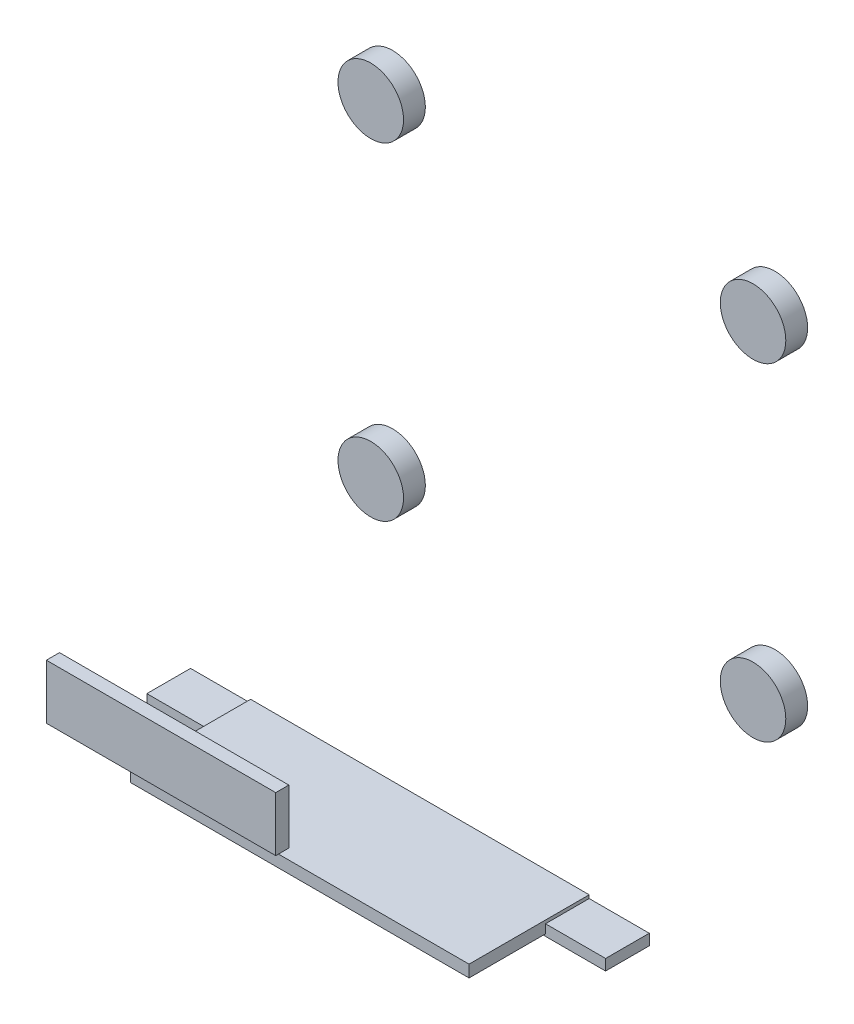
SolidWorks part; units mm, degrees
ref_plane "前视基准面" through (0, 0, 0) normal (0, 0, 1) x (1, 0, 0)
ref_plane "上视基准面" through (0, 0, 0) normal (0, 1, 0) x (1, 0, 0)
ref_plane "右视基准面" through (0, 0, 0) normal (1, 0, 0) x (0, 0, -1)
other "Configuration Table"
sketch "草图1" plane through (0, 0, 0) normal (0, 0, 1) x (1, 0, 0)
  line L1 (-31, -52.1) -> (31, -52.1)
  line L2 (-31, -52.1) -> (-31, -49.9)
  line L3 (-31, -49.9) -> (31, -49.9)
  line L4 (31, -52.1) -> (31, -49.9)
  line L5 (-31, -52.1) -> (31, -49.9) construction
  line L6 (-31, -49.9) -> (31, -52.1) construction
  point P0 (0, -51)
extrude "front face trim around HC-SR04 eye window" add sketch "草图1" along normal blind 22 from offset 26 separate body
sketch "草图2" plane through (0, 0, 0) normal (0, 0, 1) x (1, 0, 0)
  line L1 (-21, -25) -> (21, -25)
  line L2 (-21, -25) -> (-21, -15)
  line L3 (-21, -15) -> (21, -15)
  line L4 (21, -25) -> (21, -15)
  line L5 (-21, -25) -> (21, -15) construction
  line L6 (-21, -15) -> (21, -25) construction
  point P0 (0, -20)
extrude "top translucent status light strip" add sketch "草图2" along normal blind 2.4 from offset 71 separate body
sketch "草图3" plane through (0, 0, 0) normal (0, 0, 1) x (1, 0, 0)
  line L1 (-42, -52.5) -> (-30, -52.5)
  line L2 (-42, -52.5) -> (-42, -50.5)
  line L3 (-42, -50.5) -> (-30, -50.5)
  line L4 (-30, -52.5) -> (-30, -50.5)
  line L5 (-42, -52.5) -> (-30, -50.5) construction
  line L6 (-42, -50.5) -> (-30, -52.5) construction
  point P0 (-36, -51.5)
extrude "left cheek decorative insert" add sketch "草图3" along normal blind 8 from offset 26 separate body
sketch "草图4" plane through (0, 0, 0) normal (0, 0, 1) x (1, 0, 0)
  line L1 (30, -52.5) -> (42, -52.5)
  line L2 (30, -52.5) -> (30, -50.5)
  line L3 (30, -50.5) -> (42, -50.5)
  line L4 (42, -52.5) -> (42, -50.5)
  line L5 (30, -52.5) -> (42, -50.5) construction
  line L6 (30, -50.5) -> (42, -52.5) construction
  point P0 (36, -51.5)
extrude "right cheek decorative insert" add sketch "草图4" along normal blind 8 from offset 26 separate body
sketch "草图5" plane through (0, 0, 0) normal (0, 0, 1) x (1, 0, 0)
  circle A0 centre (-35, -30) radius 6
extrude "rubber foot 1" add sketch "草图5" along normal blind 4 from offset 4 separate body
sketch "草图6" plane through (0, 0, 0) normal (0, 0, 1) x (1, 0, 0)
  circle A0 centre (35, -30) radius 6
extrude "rubber foot 2" add sketch "草图6" along normal blind 4 from offset 4 separate body
sketch "草图7" plane through (0, 0, 0) normal (0, 0, 1) x (1, 0, 0)
  circle A0 centre (-35, 30) radius 6
extrude "rubber foot 3" add sketch "草图7" along normal blind 4 from offset 4 separate body
sketch "草图8" plane through (0, 0, 0) normal (0, 0, 1) x (1, 0, 0)
  circle A0 centre (35, 30) radius 6
extrude "rubber foot 4" add sketch "草图8" along normal blind 4 from offset 4 separate body
